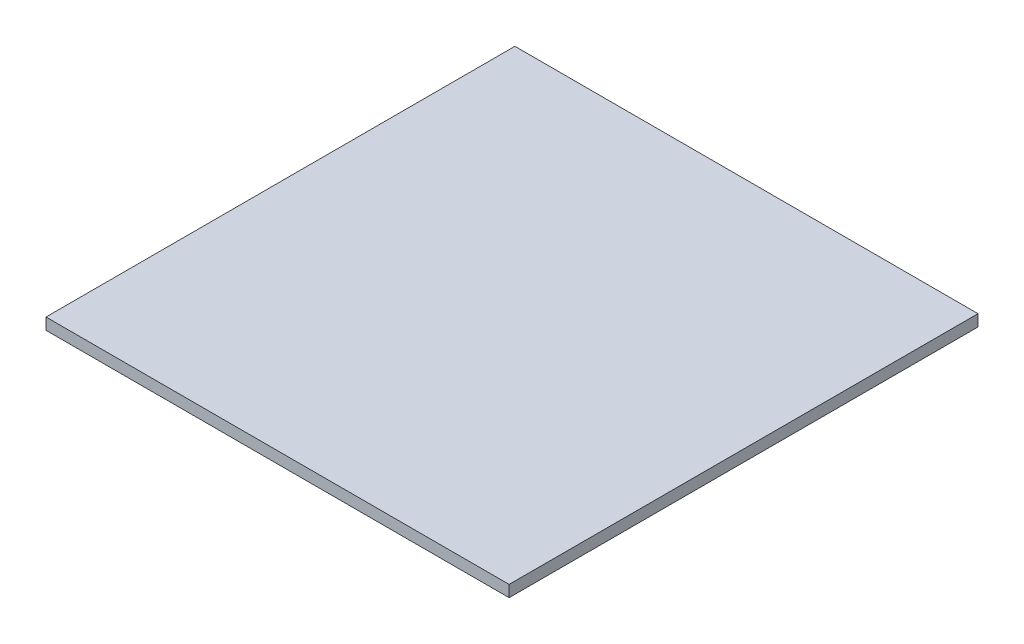
SolidWorks part; units mm, degrees
ref_plane "Front Plane" through (0, 0, 0) normal (0, 0, 1) x (1, 0, 0)
ref_plane "Top Plane" through (0, 0, 0) normal (0, 1, 0) x (1, 0, 0)
ref_plane "Right Plane" through (0, 0, 0) normal (1, 0, 0) x (0, 0, -1)
sketch "Sketch1" plane through (0, 0, 0) normal (0, 1, 0) x (1, 0, 0)
  line L1 (0, 0) -> (482, 0)
  line L2 (0, 0) -> (0, 488)
  line L3 (0, 488) -> (482, 488)
  line L4 (482, 0) -> (482, 488)
  dimension "D1" = 488
  dimension "D2" = 482
extrude "Boss-Extrude1" add sketch "Sketch1" along normal blind 12
